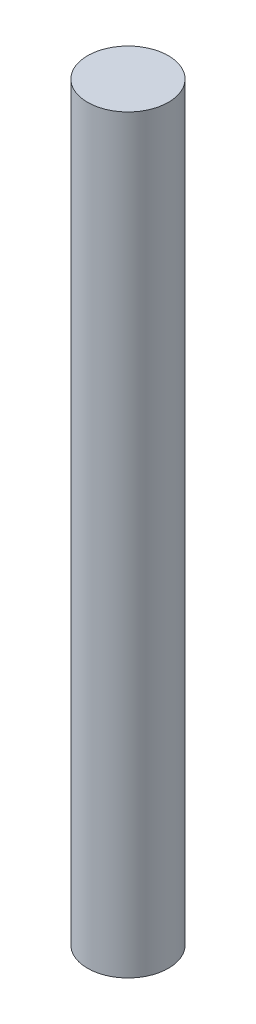
SolidWorks part; units mm, degrees
ref_plane "Front Plane" through (0, 0, 0) normal (0, 0, 1) x (1, 0, 0)
ref_plane "Top Plane" through (0, 0, 0) normal (0, 1, 0) x (1, 0, 0)
ref_plane "Right Plane" through (0, 0, 0) normal (1, 0, 0) x (0, 0, -1)
sketch "Sketch1" plane through (0, 0, 0) normal (0, 1, 0) x (1, 0, 0)
  circle A0 centre (0, 0) radius 1.25
  dimension "D1" = 2.5
extrude "Boss-Extrude1" add sketch "Sketch1" along normal blind 23.2
